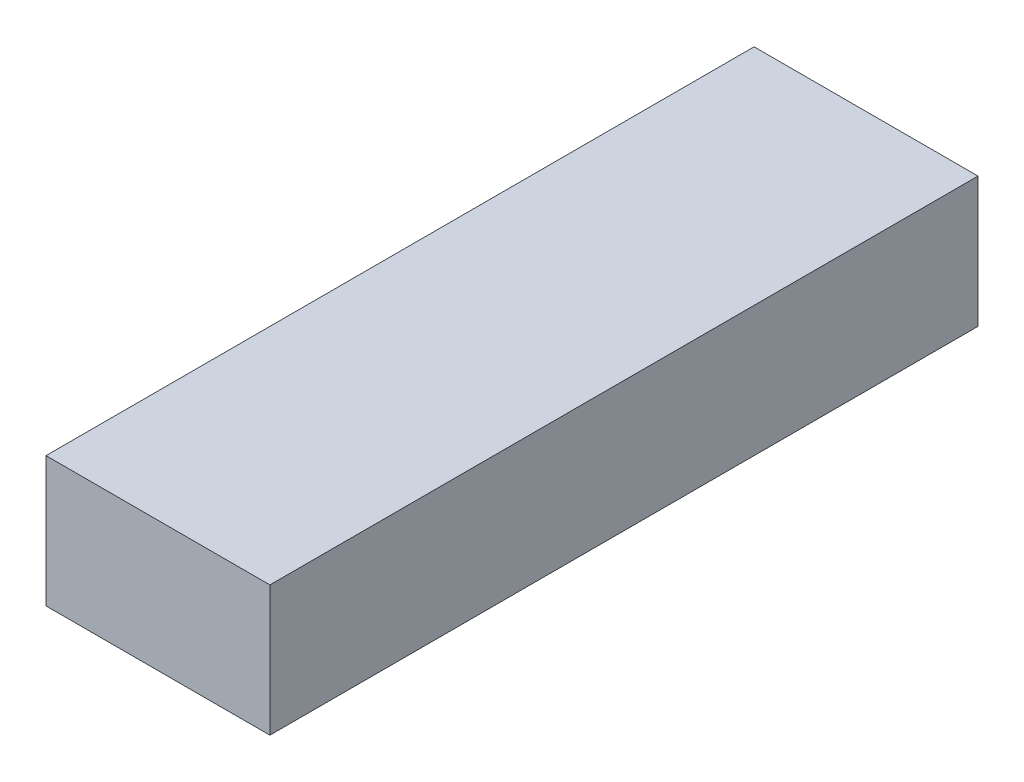
SolidWorks part; units mm, degrees
ref_plane "Front Plane" through (0, 0, 0) normal (0, 0, 1) x (1, 0, 0)
ref_plane "Top Plane" through (0, 0, 0) normal (0, 1, 0) x (1, 0, 0)
ref_plane "Right Plane" through (0, 0, 0) normal (1, 0, 0) x (0, 0, -1)
sketch "Sketch1" plane through (0, 0, 0) normal (0, 1, 0) x (1, 0, 0)
  line L1 (0, 0) -> (43, 0)
  line L2 (0, 0) -> (0, 136)
  line L3 (0, 136) -> (43, 136)
  line L4 (43, 0) -> (43, 136)
  dimension "D1" = 136
  dimension "D2" = 43
extrude "Boss-Extrude1" add sketch "Sketch1" along normal blind 25
